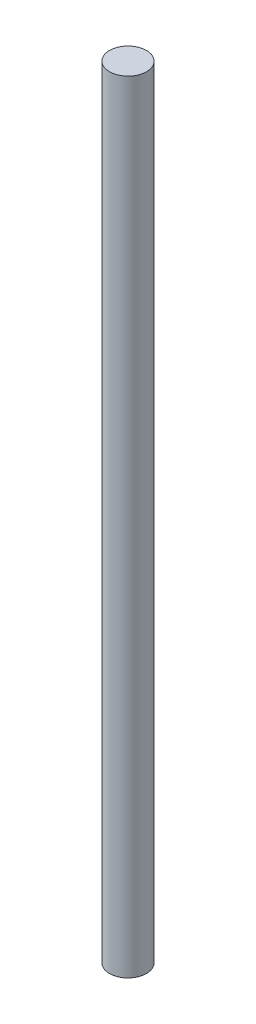
SolidWorks part; units mm, degrees
ref_plane "Front Plane" through (0, 0, 0) normal (0, 0, 1) x (1, 0, 0)
ref_plane "Top Plane" through (0, 0, 0) normal (0, 1, 0) x (1, 0, 0)
ref_plane "Right Plane" through (0, 0, 0) normal (1, 0, 0) x (0, 0, -1)
sketch "Sketch1" plane through (0, 0, 0) normal (0, 1, 0) x (1, 0, 0)
  circle A0 centre (0, 0) radius 2.6
  dimension "D1" = 5.2
extrude "Boss-Extrude1" add sketch "Sketch1" along normal blind 110
